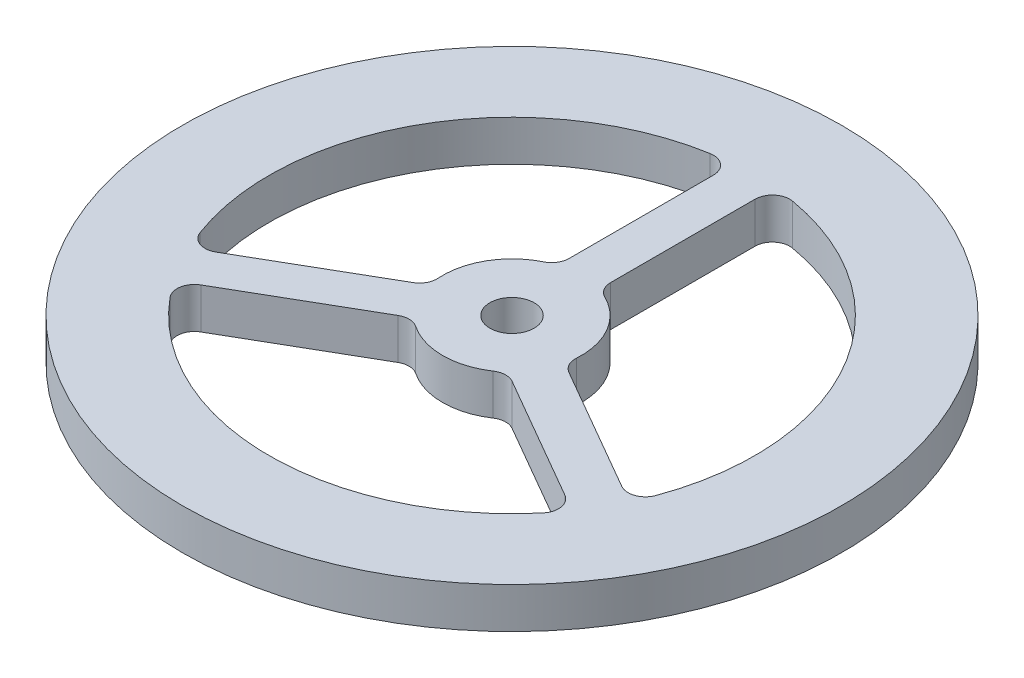
SolidWorks part; units mm, degrees
material "AISI 304"
ref_plane "Front Plane" through (0, 0, 0) normal (0, 0, 1) x (1, 0, 0)
ref_plane "Top Plane" through (0, 0, 0) normal (0, 1, 0) x (1, 0, 0)
ref_plane "Right Plane" through (0, 0, 0) normal (1, 0, 0) x (0, 0, -1)
sketch "Sketch1" plane through (0, 0, 0) normal (0, 1, 0) x (1, 0, 0)
  line L0 (2.4, 8.98) -> (2.4, 25.625)
  line L1 (-2.4, 8.98) -> (-2.4, 25.625)
  line L2 (8.9769, -2.4115) -> (23.3919, -10.734)
  line L3 (6.5769, -6.5684) -> (20.9919, -14.891)
  line L4 (-6.5769, -6.5684) -> (-20.9919, -14.891)
  line L5 (-8.9769, -2.4115) -> (-23.3919, -10.734)
  arc A0 (-21.5297, -17.9017) -> (21.5297, -17.9017) centre (0, 0) ccw
  circle A1 centre (0, 0) radius 38
  arc A2 (26.2682, -9.6944) -> (4.7385, 27.5961) centre (0, 0) ccw
  arc A3 (-4.7385, 27.5961) -> (-26.2682, -9.6944) centre (0, 0) ccw
  arc A4 (-3.52, 7.184) -> (-7.9815, -0.5436) centre (0, 0) ccw
  arc A5 (7.9815, -0.5436) -> (3.52, 7.184) centre (0, 0) ccw
  arc A6 (-4.4615, -6.6404) -> (4.4615, -6.6404) centre (0, 0) ccw
  circle A7 centre (0, 0) radius 2.55
  arc A8 (-2.4, 25.625) -> (-4.7385, 27.5961) centre (-4.4, 25.625) ccw
  arc A9 (2.4, 25.625) -> (4.7385, 27.5961) centre (4.4, 25.625) cw
  arc A10 (-23.3919, -10.734) -> (-26.2682, -9.6944) centre (-24.3919, -9.002) cw
  arc A11 (-20.9919, -14.891) -> (-21.5297, -17.9017) centre (-19.9919, -16.623) ccw
  arc A12 (20.9919, -14.891) -> (21.5297, -17.9017) centre (19.9919, -16.623) cw
  arc A13 (23.3919, -10.734) -> (26.2682, -9.6944) centre (24.3919, -9.002) ccw
  arc A14 (-2.4, 8.98) -> (-3.52, 7.184) centre (-4.4, 8.98) cw
  arc A15 (3.52, 7.184) -> (2.4, 8.98) centre (4.4, 8.98) cw
  arc A16 (-8.9769, -2.4115) -> (-7.9815, -0.5436) centre (-9.9769, -0.6795) ccw
  arc A17 (-6.5769, -6.5684) -> (-4.4615, -6.6404) centre (-5.5769, -8.3005) cw
  arc A18 (6.5769, -6.5684) -> (4.4615, -6.6404) centre (5.5769, -8.3005) ccw
  arc A19 (8.9769, -2.4115) -> (7.9815, -0.5436) centre (9.9769, -0.6795) cw
  dimension "D1" = 3
extrude "Boss-Extrude1" add sketch "Sketch1" along normal blind 4.7
